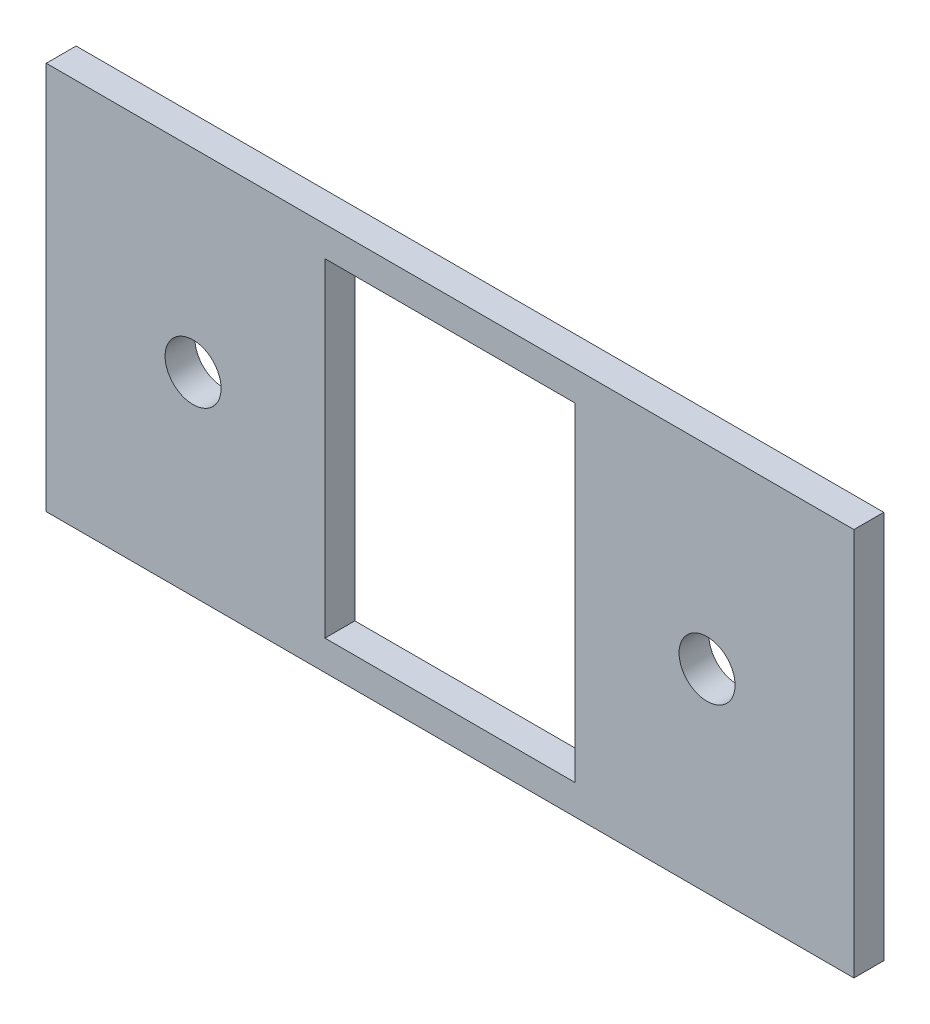
SolidWorks part; units mm, degrees
material "1060 Alloy"
ref_plane "Front Plane" through (0, 0, 0) normal (0, 0, 1) x (1, 0, 0)
ref_plane "Top Plane" through (0, 0, 0) normal (0, 1, 0) x (1, 0, 0)
ref_plane "Right Plane" through (0, 0, 0) normal (1, 0, 0) x (0, 0, -1)
sketch "Sketch1" plane through (0, 0, 0) normal (0, 0, 1) x (1, 0, 0)
  line L0 (0, 0) -> (0, 26) construction
  line L3 (-27.0353, 26) -> (27.0353, 26)
  line L4 (-27.0353, 26) -> (-27.0353, 0)
  line L5 (-27.0353, 0) -> (27.0353, 0)
  line L6 (27.0353, 26) -> (27.0353, 0)
  line L26 (-8.375, 2) -> (8.375, 2)
  line L27 (8.375, 2) -> (8.375, 24)
  line L28 (8.375, 24) -> (-8.375, 24)
  line L29 (-8.375, 24) -> (-8.375, 2)
  circle A1 centre (17.2051, 13) radius 1.875
  circle A3 centre (-17.2051, 13) radius 1.875
extrude "Boss-Extrude1" add sketch "Sketch1" along normal blind 2
